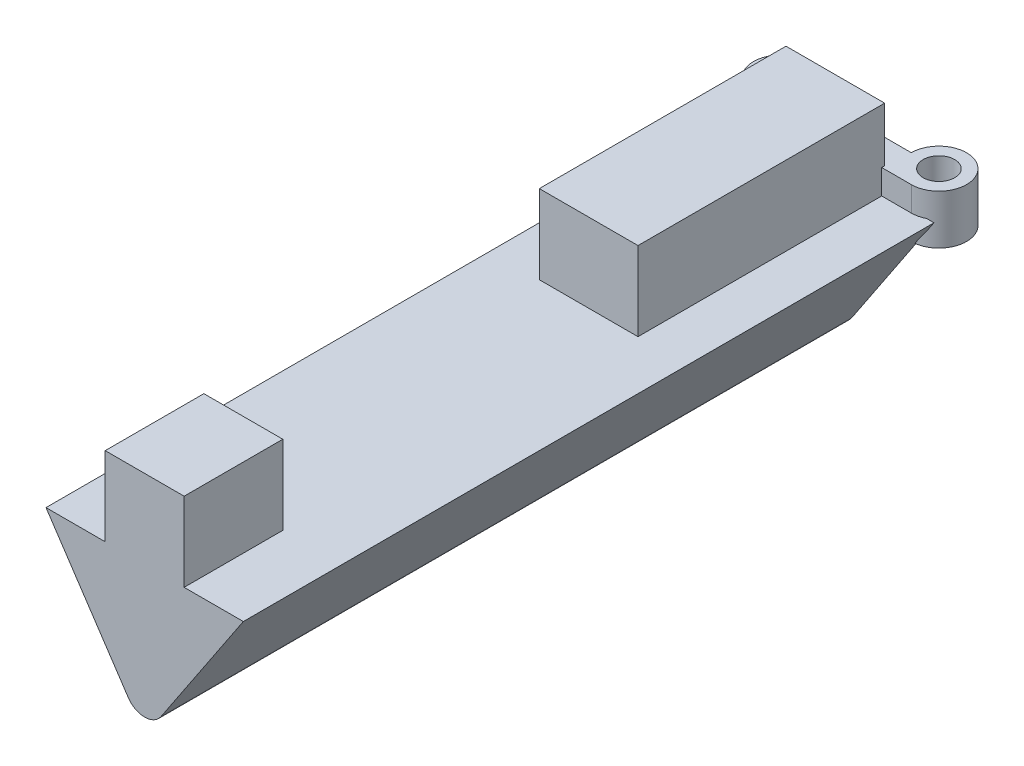
SolidWorks part; units mm, degrees
ref_plane "前视基准面" through (0, 0, 0) normal (0, 0, 1) x (1, 0, 0)
ref_plane "上视基准面" through (0, 0, 0) normal (0, 1, 0) x (1, 0, 0)
ref_plane "右视基准面" through (0, 0, 0) normal (1, 0, 0) x (0, 0, -1)
sketch "草图1" plane through (0, 0, 0) normal (0, 0, 1) x (1, 0, 0)
  line L0 (0, -15) -> (10, 0)
  line L1 (10, 0) -> (-10, 0)
  line L2 (-10, 0) -> (0, -15)
  line L3 (0, 23.0028) -> (0, 0) construction
  point P4 (0, 0)
extrude "凸台-拉伸1" add sketch "草图1" along normal blind 70
sketch "草图2" plane through (0, 0, 0) normal (0, 0, 1) x (1, 0, 0)
  line L0 (0, 0) -> (0, 8) construction
  line L1 (0, 8) -> (-5, 8) construction
  line L3 (5, 0) -> (-5, 0)
  line L4 (5, 0) -> (5, 8)
  line L5 (5, 8) -> (-5, 8)
  line L6 (-5, 0) -> (-5, 8)
  line L7 (5, 0) -> (-5, 8) construction
  line L8 (5, 8) -> (-5, 0) construction
  point P3 (0, 4)
extrude "凸台-拉伸2" add sketch "草图2" along normal blind 25
sketch "草图3" plane through (0, 0, 70) normal (0, 0, 1) x (1, 0, 0)
  line L0 (0, 0) -> (0, 8) construction
  line L1 (5, 8) -> (-5, 8) construction
  line L3 (4, 0) -> (-4, 0)
  line L4 (4, 0) -> (4, 8)
  line L5 (4, 8) -> (-4, 8)
  line L6 (-4, 0) -> (-4, 8)
  line L7 (4, 0) -> (-4, 8) construction
  line L8 (4, 8) -> (-4, 0) construction
  point P5 (0, 4)
extrude "凸台-拉伸3" add sketch "草图3" against normal blind 10
sketch "草图5" plane through (0, 0, 0) normal (0, -1, 0) x (1, 0, 0)
  line L0 (-5.2, -2.5) -> (5.2, -2.5)
  line L2 (0, 0) -> (0, -7.3568) construction
  line L3 (-8, 0.3) -> (8, 0.3)
  circle A0 centre (-8, -2.5) radius 1.6
  arc A1 (-8, 0.3) -> (-5.2, -2.5) centre (-8, -2.5) ccw
  arc A2 (8, 0.3) -> (5.2, -2.5) centre (8, -2.5) cw
  circle A3 centre (8, -2.5) radius 1.6
extrude "凸台-拉伸4" add sketch "草图5" against normal mid plane 5
fillet "圆角1" radius 2 1 edges at (0, -15, 35)
